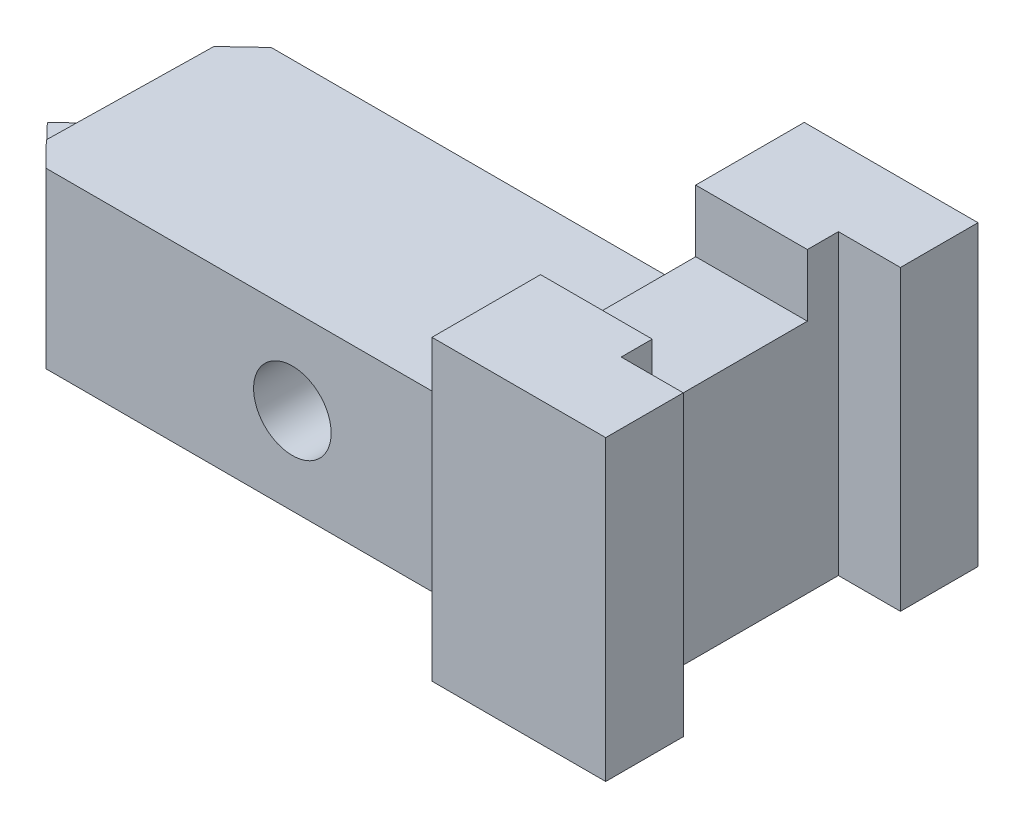
SolidWorks part; units mm, degrees
ref_plane "Front Plane" through (0, 0, 0) normal (0, 0, 1) x (1, 0, 0)
ref_plane "Top Plane" through (0, 0, 0) normal (0, 1, 0) x (1, 0, 0)
ref_plane "Right Plane" through (0, 0, 0) normal (1, 0, 0) x (0, 0, -1)
sketch "Sketch1" plane through (0, 0, 0) normal (0, 0, 1) x (1, 0, 0)
  line L1 (0, 0) -> (28, 0)
  line L2 (0, 0) -> (0, 48)
  line L3 (0, 48) -> (28, 48)
  line L4 (28, 0) -> (28, 48)
  line L5 (0, 0) -> (28, 48) construction
  line L6 (0, 48) -> (28, 0) construction
  point P4 (14, 24)
  dimension "D1" = 48
  dimension "D2" = 28
extrude "Boss-Extrude3" add sketch "Sketch1" along normal blind 60
sketch "Sketch6" plane through (0, 48, 0) normal (0, 1, 0) x (1, 0, 0)
  line L0 (28, -60) -> (28, 0) construction
  line L1 (28, -12.5) -> (18, -12.5)
  line L2 (28, -12.5) -> (28, -47.5)
  line L3 (28, -47.5) -> (18, -47.5)
  line L4 (18, -12.5) -> (18, -47.5)
  line L5 (28, -12.5) -> (18, -47.5) construction
  line L6 (28, -47.5) -> (18, -12.5) construction
  line L7 (0, 0) -> (28, 0) construction
  point P4 (23, -30)
  dimension "D1" = 10
  dimension "D2" = 35
  dimension "D3" = 12.5
extrude "Cut-Extrude7" cut sketch "Sketch6" against normal blind 48
sketch "Sketch7" plane through (0, 0, 0) normal (-1, 0, 0) x (0, 0, 1)
  line L0 (60, 48) -> (0, 48) construction
  line L1 (17.5, 48) -> (42.5, 48)
  line L2 (17.5, 48) -> (17.5, 38)
  line L3 (17.5, 38) -> (42.5, 38)
  line L4 (42.5, 48) -> (42.5, 38)
  line L5 (17.5, 48) -> (42.5, 38) construction
  line L6 (17.5, 38) -> (42.5, 48) construction
  line L7 (0, 48) -> (0, 0) construction
  point P4 (30, 43)
  dimension "D1" = 10
  dimension "D2" = 25
  dimension "D3" = 17.5
extrude "Cut-Extrude8" cut sketch "Sketch7" against normal blind 48
sketch "Sketch8" plane through (0, 0, 0) normal (-1, 0, 0) x (0, 0, 1)
  line L0 (60, 0) -> (0, 0) construction
  line L1 (12.5, 0) -> (47.5, 0)
  line L2 (12.5, 0) -> (12.5, 28)
  line L3 (12.5, 28) -> (47.5, 28)
  line L4 (47.5, 0) -> (47.5, 28)
  line L5 (12.5, 0) -> (47.5, 28) construction
  line L6 (12.5, 28) -> (47.5, 0) construction
  line L7 (0, 48) -> (0, 0) construction
  point P4 (30, 14)
  dimension "D1" = 28
  dimension "D2" = 35
  dimension "D3" = 12.5
extrude "Boss-Extrude4" add sketch "Sketch8" along normal blind 92
sketch "Sketch9" plane through (0, 0, 47.5) normal (0, 0, 1) x (1, 0, 0)
  line L0 (0, 48) -> (0, 0) construction
  line L1 (-92, 0) -> (0, 0) construction
  circle A0 centre (-35, 14) radius 6.25
  dimension "D2" = 12.5
  dimension "D1" = 35
  dimension "D3" = 14
extrude "Cut-Extrude9" cut sketch "Sketch9" against normal blind 59
sketch "Sketch16" plane through (0, 28, 0) normal (0, 1, 0) x (1, 0, 0)
  line L0 (-92, -30) -> (-73.4085, -12.5)
  line L1 (-92, -47.5) -> (-92, -12.5) construction
  line L2 (-92, -12.5) -> (0, -12.5) construction
  line L3 (-73.4085, -12.5) -> (-92, -12.5)
  line L4 (-92, -12.5) -> (-92, -30)
  point P8 (0, 0)
  point P14 (0, 0)
  point P15 (-92, -30)
extrude "Cut-Extrude12" cut sketch "Sketch16" against normal blind 59
sketch "Sketch17" plane through (0, 28, 0) normal (0, 1, 0) x (1, 0, 0)
  line L0 (-92, -30) -> (-92, -47.5)
  line L1 (-92, -47.5) -> (-74.7054, -47.5)
  line L2 (-92, -47.5) -> (0, -47.5) construction
  line L3 (-74.7054, -47.5) -> (-92, -30)
extrude "Cut-Extrude13" cut sketch "Sketch17" against normal blind 59
sketch "Sketch18" plane through (0, 28, 0) normal (0, 1, 0) x (1, 0, 0)
  line L1 (-92, -30) -> (-78.6445, -43.5141)
  line L3 (-74.7054, -47.5) -> (-92, -30) construction
  line L5 (-92, -30) -> (-78.165, -16.9773)
  line L6 (-92, -30) -> (-73.4085, -12.5) construction
  line L7 (-78.6445, -43.5141) -> (-78.165, -16.9773)
  dimension "D1" = 19
  dimension "D2" = 19
extrude "Cut-Extrude18" cut sketch "Sketch18" against normal blind 11
